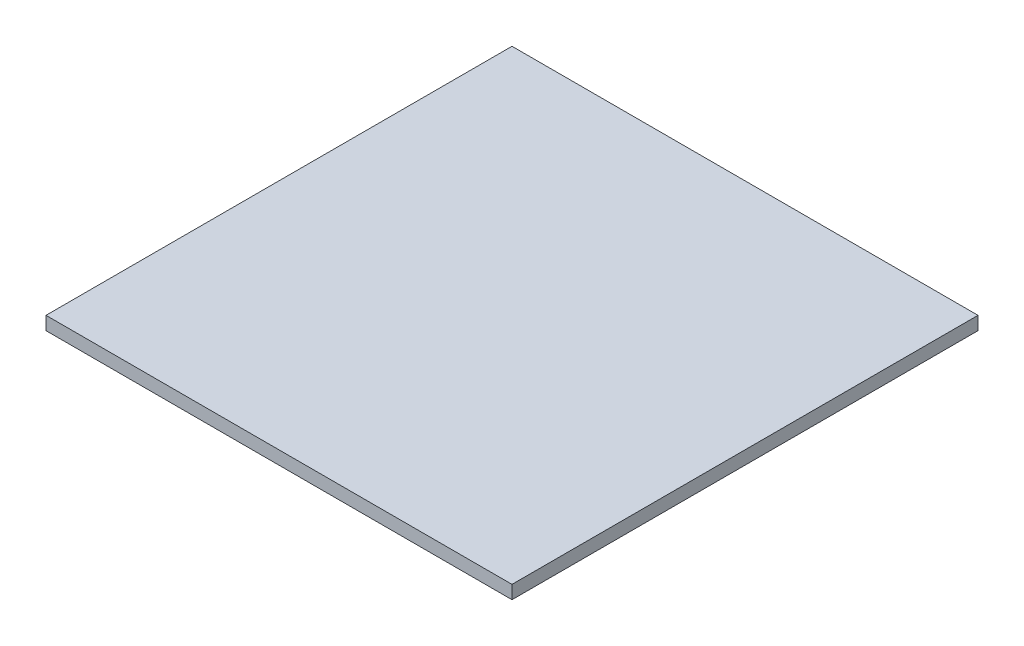
SolidWorks part; units mm, degrees
ref_plane "Front Plane" through (0, 0, 0) normal (0, 0, 1) x (1, 0, 0)
ref_plane "Top Plane" through (0, 0, 0) normal (0, 1, 0) x (1, 0, 0)
ref_plane "Right Plane" through (0, 0, 0) normal (1, 0, 0) x (0, 0, -1)
sketch "Sketch1" plane through (0, 0, 0) normal (0, 1, 0) x (1, 0, 0)
  line L1 (0, 0) -> (14, 0)
  line L2 (0, 0) -> (0, 14)
  line L3 (0, 14) -> (14, 14)
  line L4 (14, 0) -> (14, 14)
  dimension "D1" = 14
  dimension "D2" = 14
extrude "Boss-Extrude1" add sketch "Sketch1" along normal blind 0.4
